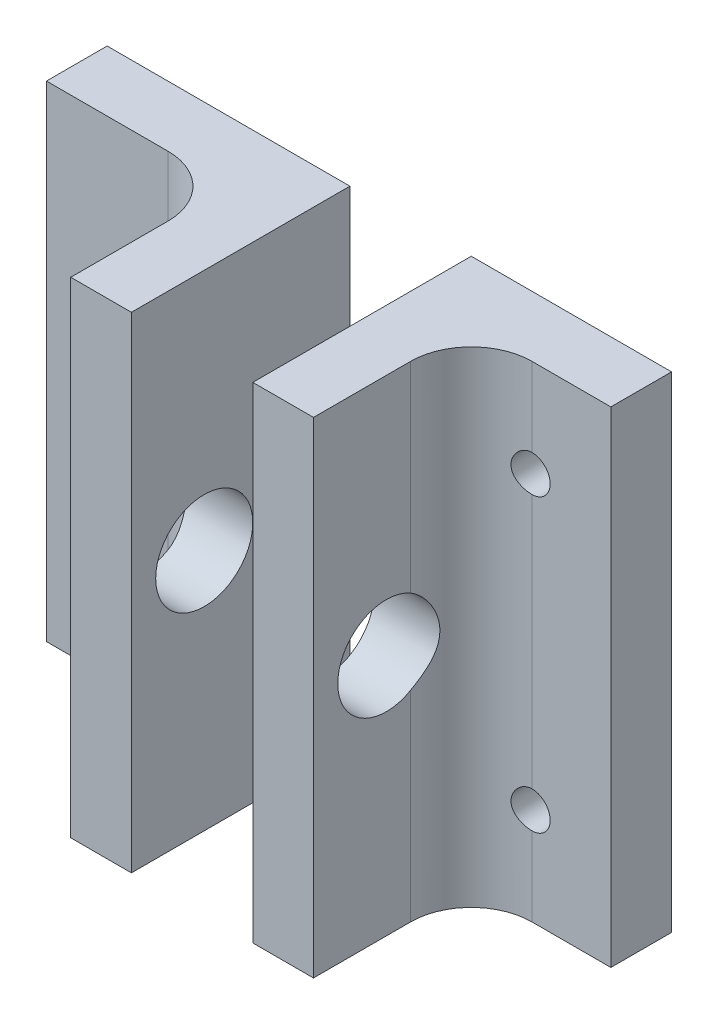
SolidWorks part; units mm, degrees
ref_plane "Front Plane" through (0, 0, 0) normal (0, 0, 1) x (1, 0, 0)
ref_plane "Top Plane" through (0, 0, 0) normal (0, 1, 0) x (1, 0, 0)
ref_plane "Right Plane" through (0, 0, 0) normal (1, 0, 0) x (0, 0, -1)
sketch "Sketch1" plane through (0, 0, 0) normal (0, 1, 0) x (1, 0, 0)
  line L0 (0, 0) -> (0, 22.4056) construction
  line L5 (-5, 18) -> (-5, 0)
  line L6 (-5, 0) -> (-10, 0)
  line L7 (-10, 0) -> (-10, 8)
  line L8 (-15, 13) -> (-25, 13)
  line L9 (-25, 13) -> (-25, 18)
  line L10 (-25, 18) -> (-5, 18)
  line L11 (25, 18) -> (5, 18)
  line L12 (25, 13) -> (25, 18)
  line L13 (15, 13) -> (25, 13)
  line L14 (10, 0) -> (10, 8)
  line L15 (5, 0) -> (10, 0)
  line L16 (5, 18) -> (5, 0)
  arc A0 (-10, 8) -> (-15, 13) centre (-15, 8) ccw
  arc A1 (10, 8) -> (15, 13) centre (15, 8) cw
  point P17 (-10, 13)
  point P20 (10, 13)
  dimension "D6" = 5
  dimension "D7" = 5
  dimension "D1" = 5
  dimension "D2" = 5
  dimension "D3" = 20
  dimension "D4" = 18
  dimension "D5" = 5
extrude "Boss-Extrude1" add sketch "Sketch1" along normal mid plane 40
sketch "Sketch2" plane through (10, 0, 0) normal (1, 0, 0) x (0, 0, -1)
  line L0 (0, 0) -> (10.468, 0) construction
  line L1 (0, 20) -> (0, -20) construction
  circle A0 centre (6, 0) radius 4
  dimension "D1" = 8
  dimension "D2" = 6
extrude "Cut-Extrude1" cut sketch "Sketch2" against normal through all both and the other way through all
sketch "Sketch3" plane through (0, 0, -18) normal (0, 0, -1) x (-1, 0, 0)
  line L0 (0, 0) -> (-28.0618, 0) construction
  line L1 (0, 0) -> (0, 31.3837) construction
  circle A0 centre (-15, -12) radius 1.5
  circle A1 centre (-15, 12) radius 1.5
  circle A2 centre (15, 12) radius 1.5
  circle A3 centre (15, -12) radius 1.5
  dimension "D1" = 3
  dimension "D3" = 30
  dimension "D2" = 24
extrude "Cut-Extrude2" cut sketch "Sketch3" against normal through all both and the other way through all
sketch "Sketch4" plane through (0, 0, -18) normal (0, 0, -1) x (-1, 0, 0)
  line L0 (-21.5, 20) -> (-21.5, -20)
  line L1 (-25, 20) -> (-5, 20) construction
  line L2 (-25, -20) -> (-5, -20) construction
  line L3 (-21.5, -20) -> (-25, -20)
  line L4 (-25, -20) -> (-25, 20)
  line L5 (-25, 20) -> (-21.5, 20)
  dimension "D1" = 3.5
extrude "Cut-Extrude3" cut sketch "Sketch4" against normal through all both and the other way through all
